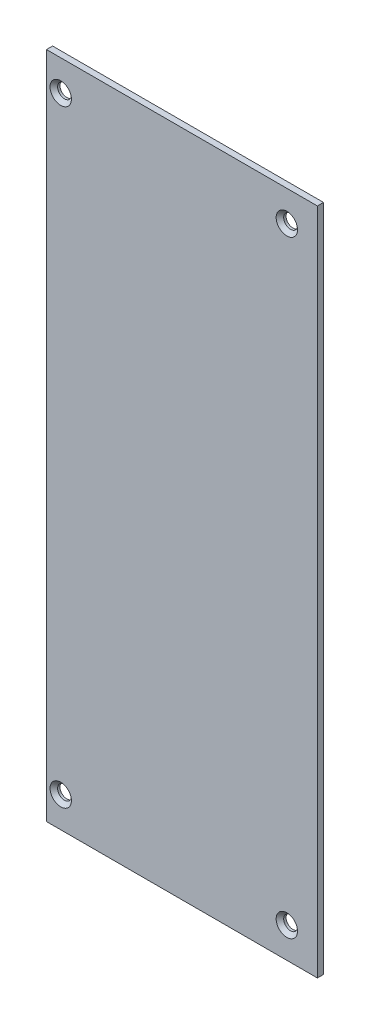
SolidWorks part; units mm, degrees
ref_plane "Front Plane" through (0, 0, 0) normal (0, 0, 1) x (1, 0, 0)
ref_plane "Top Plane" through (0, 0, 0) normal (0, 1, 0) x (1, 0, 0)
ref_plane "Right Plane" through (0, 0, 0) normal (1, 0, 0) x (0, 0, -1)
sketch "Sketch1" plane through (0, 0, 0) normal (0, 0, 1) x (1, 0, 0)
  line L1 (-42.2005, 104.14) -> (42.2005, 104.14)
  line L2 (-42.2005, 104.14) -> (-42.2005, -104.14)
  line L3 (-42.2005, -104.14) -> (42.2005, -104.14)
  line L4 (42.2005, 104.14) -> (42.2005, -104.14)
  point P4 (0, 104.14)
  point P6 (-42.2005, 0)
  dimension "D1" = 84.401
  dimension "D2" = 208.28
extrude "Boss-Extrude1" add sketch "Sketch1" along normal blind 1.905
sketch "Sketch2" plane through (0, 0, 1.905) normal (0, 0, 1) x (1, 0, 0)
  line L0 (-42.2005, -94.615) -> (-37.7555, -94.615) construction
  line L1 (-42.2005, 104.14) -> (-42.2005, -104.14) construction
  line L2 (-37.7555, -94.615) -> (-37.7555, -104.14) construction
  line L3 (-42.2005, -104.14) -> (42.2005, -104.14) construction
  line L4 (-42.2005, 94.615) -> (-37.7555, 94.615) construction
  line L5 (-37.7555, 94.615) -> (-37.7555, 104.14) construction
  line L6 (42.2005, 104.14) -> (-42.2005, 104.14) construction
  line L7 (42.2005, -104.14) -> (42.2005, 104.14) construction
  line L8 (32.6755, 94.615) -> (32.6755, 104.14) construction
  line L9 (32.6755, -94.615) -> (32.6755, -104.14) construction
  line L10 (32.6755, 94.615) -> (42.2005, 94.615) construction
  line L11 (32.6755, -94.615) -> (42.2005, -94.615) construction
  point P0 (-37.7555, 94.615)
  point P1 (-37.7555, -94.615)
  point P11 (32.6755, -94.615)
  point P15 (32.6755, 94.615)
  dimension "D2" = 9.525
  dimension "D3" = 4.445
hole_wizard "#6 Clearance Hole1" positions "Sketch2" profile "Sketch3" hole size "#6" standard "ANSI Inch" end condition up to next
sketch "Sketch3" plane through (-37.7555, 94.615, 1.905) normal (1, 0, 0) x (0, -1, 0)
  line L0 (0, 0) -> (0, 1.905)
  line L1 (0, 1.905) -> (2.1526, 1.905)
  line L2 (2.1526, 1.905) -> (2.1526, 1.1748)
  line L3 (2.1526, 1.1748) -> (3.3274, 0)
  line L5 (3.3274, 0) -> (0, 0)
  line L6 (-2.1526, 1.1747) -> (-3.3274, 0) construction
  line L11 (0, -6.35) -> (0, 107.95) construction
  dimension "Thru Hole Dia." = 4.3053
  dimension "Thru Hole Depth" = 1.905
  dimension "Near C'Sink Dia." = 6.6548
  dimension "Near C'Sink Angle" = 90
sketch "Sketch4" plane through (0, 0, 0) normal (0, 0, -1) x (-1, 0, 0)
  line L5 (-42.2005, 104.14) -> (42.2005, 104.14) construction
  line L6 (33.7338, -3.81) -> (42.2005, -3.81)
  line L7 (33.7338, -3.81) -> (33.7338, -12.2767)
  line L8 (33.7338, -12.2767) -> (42.2005, -12.2767)
  line L9 (42.2005, -3.81) -> (42.2005, -12.2767)
  line L10 (33.7338, -78.74) -> (42.2005, -78.74)
  line L11 (33.7338, -78.74) -> (33.7338, -87.2067)
  line L12 (33.7338, -87.2067) -> (42.2005, -87.2067)
  line L13 (42.2005, -78.74) -> (42.2005, -87.2067)
  line L14 (42.2005, -104.14) -> (-42.2005, -104.14) construction
  line L15 (42.2005, 104.14) -> (42.2005, -104.14) construction
  point P0 (42.2005, -78.74)
  dimension "D1" = 8.4667
  dimension "D3" = 16.9333
  dimension "D4" = 107.95
extrude "Boss-Extrude2" add sketch "Sketch4" along normal blind 9.525
sketch "Sketch5" plane through (-42.2005, 0, 0) normal (1, 0, 0) x (0, 0, -1)
  line L0 (2.1167, -82.9733) -> (5.2917, -79.7983)
  line L1 (2.1167, -82.9733) -> (5.2917, -86.1483)
  line L2 (5.2917, -79.7983) -> (8.4667, -82.9733)
  line L3 (5.2917, -86.1483) -> (8.4667, -82.9733)
  line L4 (2.1167, -82.9733) -> (8.4667, -82.9733) construction
  line L5 (5.2917, -79.7983) -> (5.2917, -86.1483) construction
  line L6 (2.1167, -8.0433) -> (5.2917, -4.8683)
  line L7 (2.1167, -8.0433) -> (5.2917, -11.2183)
  line L8 (5.2917, -4.8683) -> (8.4667, -8.0433)
  line L9 (5.2917, -11.2183) -> (8.4667, -8.0433)
  line L10 (2.1167, -8.0433) -> (8.4667, -8.0433) construction
  line L11 (5.2917, -4.8683) -> (5.2917, -11.2183) construction
  line L21 (9.525, -78.74) -> (9.525, -87.2067) construction
  line L22 (9.525, -3.81) -> (9.525, -12.2767) construction
  point P1 (5.2917, -82.9733)
  point P2 (5.2917, -8.0433)
  point P20 (9.525, -82.9733)
  point P23 (9.525, -8.0433)
  dimension "D1" = 4.2333
extrude "Cut-Extrude3" cut sketch "Sketch5" along normal blind 6.35
chamfer "Chamfer1" distance 0.635 angle 45 16 edges at (-35.8505, -81.3858, -3.7042) (-35.8505, -81.3858, -6.8792) (-35.8505, -84.5608, -6.8792) (-35.8505, -84.5608, -3.7042) (-35.8505, -9.6308, -6.8792) (-35.8505, -6.4558, -6.8792) (-35.8505, -6.4558, -3.7042) (-35.8505, -9.6308, -3.7042) (-42.2005, -84.5608, -6.8792) (-42.2005, -84.5608, -3.7042) (-42.2005, -81.3858, -3.7042) (-42.2005, -81.3858, -6.8792) (-42.2005, -9.6308, -6.8792) (-42.2005, -9.6308, -3.7042) (-42.2005, -6.4558, -3.7042) (-42.2005, -6.4558, -6.8792)
